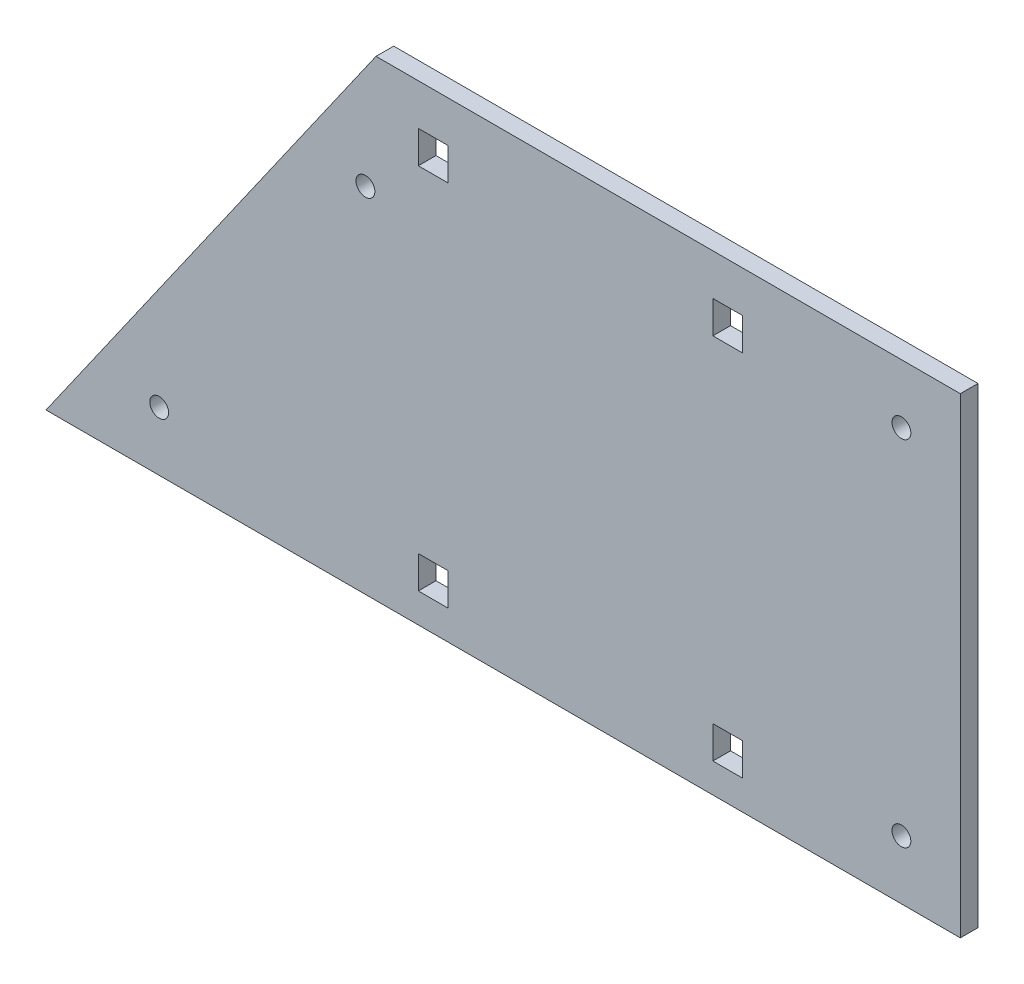
SolidWorks part; units mm, degrees
ref_plane "前视基准面" through (0, 0, 0) normal (0, 0, 1) x (1, 0, 0)
ref_plane "上视基准面" through (0, 0, 0) normal (0, 1, 0) x (1, 0, 0)
ref_plane "右视基准面" through (0, 0, 0) normal (1, 0, 0) x (0, 0, -1)
sketch "草图1" plane through (0, 0, 0) normal (0, 0, 1) x (1, 0, 0)
  line L0 (137.75, -25.25) -> (38.57, -25.25)
  line L1 (38.57, -25.25) -> (-17.4466, -105.25)
  line L2 (-17.4466, -105.25) -> (137.75, -105.25)
  line L3 (137.75, -25.25) -> (137.75, -105.25)
  circle A0 centre (36.7736, -45.25) radius 1.6
  circle A1 centre (1.7632, -95.25) radius 1.6
  circle A2 centre (127.75, -35.25) radius 1.6
  circle A3 centre (127.75, -95.25) radius 1.6
extrude "凸台-拉伸2" add sketch "草图1" along normal blind 3
sketch "草图2" plane through (0, 0, 3) normal (0, 0, 1) x (1, 0, 0)
  line L0 (100.75, -100.25) -> (100.75, -95.4867) construction
  line L1 (100.75, -100.25) -> (95.75, -100.25)
  line L2 (100.75, -100.25) -> (100.75, -94.75)
  line L3 (100.75, -94.75) -> (95.75, -94.75)
  line L4 (95.75, -100.25) -> (95.75, -94.75)
  line L5 (50.75, -100.25) -> (45.75, -100.25)
  line L6 (50.75, -100.25) -> (50.75, -94.75)
  line L7 (50.75, -94.75) -> (45.75, -94.75)
  line L8 (45.75, -100.25) -> (45.75, -94.75)
  line L9 (95.75, -100.25) -> (95.75, -95.4867) construction
  line L10 (95.75, -100.25) -> (88.7275, -100.25) construction
  line L11 (50.75, -95.4867) -> (50.75, -100.25) construction
  line L12 (45.75, -100.25) -> (38.8174, -100.25) construction
  line L13 (45.75, -95.4867) -> (45.75, -100.25) construction
  dimension "D1" = 5.5
  dimension "D2" = 5.5
extrude "切除-拉伸1" cut sketch "草图2" against normal blind 5
pattern_linear "阵列(线性)1" count 2 spacing 62.5 along (0, 1, 0) of "切除-拉伸1"
